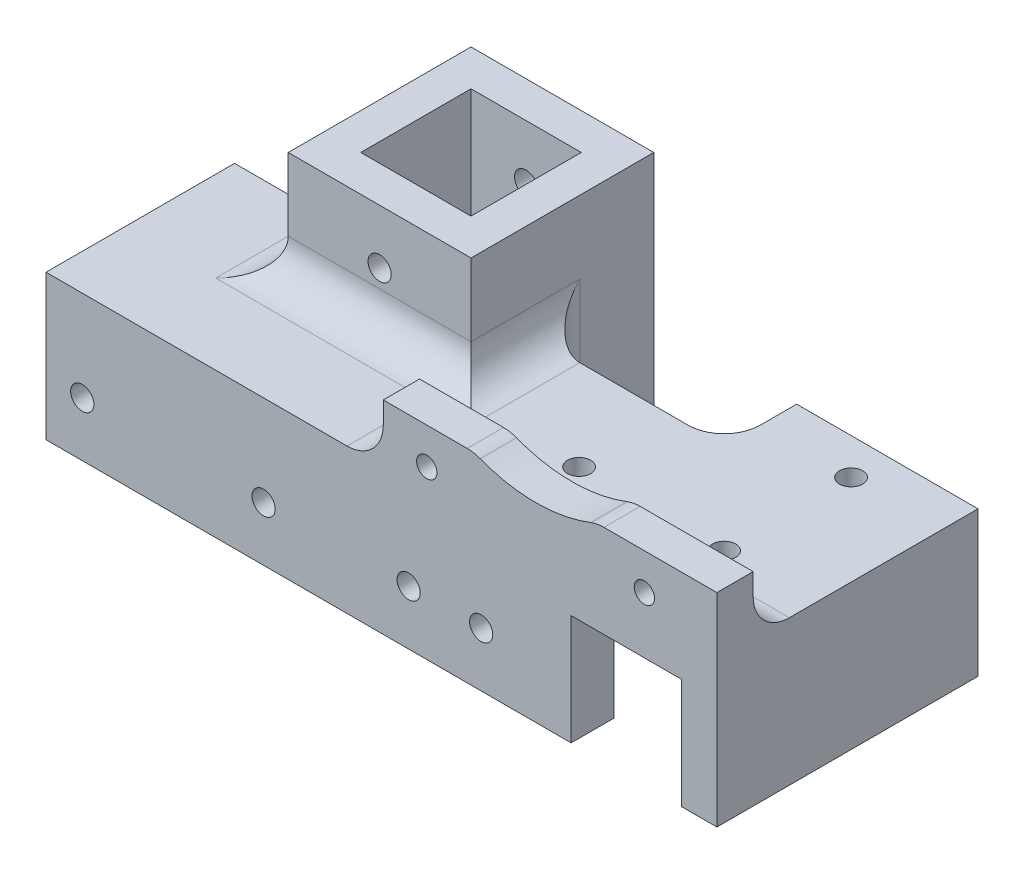
SolidWorks part; units mm, degrees
material "PLA"
ref_plane "前视基准面" through (0, 0, 0) normal (0, 0, 1) x (1, 0, 0)
ref_plane "上视基准面" through (0, 0, 0) normal (0, 1, 0) x (1, 0, 0)
ref_plane "右视基准面" through (0, 0, 0) normal (1, 0, 0) x (0, 0, -1)
sketch "草图1" plane through (0, 0, 0) normal (0, 1, 0) x (1, 0, 0)
  line L3 (-30, 12.5) -> (-12.6, 12.5)
  line L4 (-7.6, 22.7) -> (7.6, 22.7)
  line L5 (-7.6, 22.7) -> (-7.6, 7.5)
  line L6 (-7.6, 7.5) -> (7.6, 7.5)
  line L7 (7.6, 22.7) -> (7.6, 7.5)
  line L8 (-7.6, 22.7) -> (7.6, 7.5) construction
  line L9 (-7.6, 7.5) -> (7.6, 22.7) construction
  line L12 (50, -13.5) -> (50, 22.5) construction
  line L14 (-12.6, 27.7) -> (-12.6, 12.5)
  line L15 (-12.6, 27.7) -> (12.6, 27.7)
  line L16 (12.6, 27.7) -> (12.6, 12.5)
  line L17 (12.6, 27.7) -> (12.6, 7.5) construction
  line L18 (12.6, 12.5) -> (37.5, 12.5)
  line L20 (-12.6, 27.7) -> (-12.6, 7.5) construction
  line L29 (-30, 12.5) -> (-30, -13.5)
  line L32 (57.5, -13.5) -> (57.5, 22.5) construction
  line L33 (42.5, -13.5) -> (42.5, 22.5) construction
  line L34 (37.5, 12.5) -> (37.5, 22.5)
  line L35 (37.5, 22.5) -> (62.5, 22.5)
  line L36 (62.5, 22.5) -> (62.5, -13.5)
  line L37 (50, -13.5) -> (50, 22.5) construction
  line L38 (57.5, -13.5) -> (57.5, 22.5) construction
  line L39 (42.5, -13.5) -> (42.5, 22.5) construction
  line L40 (-30, -13.5) -> (62.5, -13.5)
  line L41 (-30, -7.5) -> (42.5, -7.5) construction
  line L42 (-30, 0) -> (50, 0) construction
  line L43 (-30, 7.5) -> (42.5, 7.5) construction
  point P9 (0, 15.1)
  dimension "D3" = 15.2
  dimension "D4" = 50
  dimension "D8" = 7.5
  dimension "D6" = 7.5
  dimension "D13" = 30
  dimension "D2" = 6
  dimension "D5" = 5
  dimension "D9" = 5
  dimension "D10" = 15
  dimension "D7" = 5
  dimension "D14" = 7.5
  dimension "D15" = 7.5
extrude "凸台-拉伸1" add sketch "草图1" along normal blind 20
sketch "草图2" plane through (0, 20, 0) normal (0, 1, 0) x (1, 0, 0)
  line L0 (7.6, 7.5) -> (7.6, 22.7) construction
  line L1 (7.6, 7.5) -> (7.6, 22.7)
  line L2 (-7.6, 7.5) -> (7.6, 7.5) construction
  line L3 (-7.6, 22.7) -> (-7.6, 7.5) construction
  line L4 (7.6, 22.7) -> (-7.6, 22.7) construction
  line L5 (-7.6, 7.5) -> (7.6, 7.5)
  line L6 (-7.6, 22.7) -> (-7.6, 7.5)
  line L7 (7.6, 22.7) -> (-7.6, 22.7)
  line L8 (-12.6, 27.7) -> (-12.6, 2.5)
  line L9 (-12.6, 2.5) -> (12.6, 2.5)
  line L10 (12.6, 2.5) -> (12.6, 27.7)
  line L11 (12.6, 27.7) -> (-12.6, 27.7)
  dimension "D1" = 5
extrude "凸台-拉伸2" add sketch "草图2" along normal blind 15
sketch "草图3" plane through (-30, 0, 0) normal (1, 0, 0) x (0, 0, -1)
  line L0 (-7.6, 0) -> (7.6, 0)
  line L1 (-7.6, 15.2) -> (7.6, 15.2)
  line L2 (-7.6, 15.2) -> (-7.6, 0)
  line L3 (-13.5, 0) -> (22.5, 0) construction
  line L4 (7.6, 15.2) -> (7.6, 0)
  point P4 (0, 15.2)
  dimension "D1" = 15.2
extrude "切除-拉伸1" cut sketch "草图3" along normal blind 80
sketch "草图4" plane through (0, 0, 13.5) normal (0, 0, 1) x (1, 0, 0)
  line L0 (-30, 7.5) -> (30, 7.5) construction
  line L2 (-30, 0) -> (62.5, 0) construction
  line L3 (0, 0) -> (0, 7.5) construction
  line L4 (0, 7.5) -> (0, 27.5) construction
  line L5 (-12.6, 35) -> (12.6, 35) construction
  line L6 (-30, 20) -> (-30, 0) construction
  circle A0 centre (0, 7.5) radius 1.6
  circle A1 centre (20, 7.5) radius 1.6
  circle A2 centre (-25, 7.5) radius 1.6
  circle A3 centre (0, 27.5) radius 1.6
  circle A4 centre (30, 7.5) radius 1.6
  dimension "D1" = 3.2
  dimension "D2" = 25
  dimension "D3" = 3.2
  dimension "D6" = 20
  dimension "D7" = 10
  dimension "D4" = 7.5
  dimension "D5" = 7.5
extrude "切除-拉伸2" cut sketch "草图4" against normal through all
fillet "圆角1" radius 5 6 edges at (12.6, 10, -12.5) (-12.6, 10, -12.5) (-12.6, 20, -7.5) (0, 20, -2.5) (12.6, 20, -7.5) (37.5, 10, -12.5)
sketch "草图5" plane through (0, 0, 13.5) normal (0, 0, 1) x (1, 0, 0)
  line L1 (42.4, 0) -> (57.6, 0)
  line L2 (42.4, 0) -> (42.4, 15.2)
  line L3 (42.4, 15.2) -> (57.6, 15.2)
  line L4 (57.6, 0) -> (57.6, 15.2)
  line L5 (-30, 0) -> (62.5, 0) construction
  point P6 (50, 0)
  dimension "D1" = 50
  dimension "D2" = 15.2
extrude "切除-拉伸3" cut sketch "草图5" against normal through all
sketch "草图7" plane through (0, 20, 0) normal (0, 1, 0) x (1, 0, 0)
  line L0 (0, 0) -> (50, 0) construction
  line L1 (50, 0) -> (50, 22.5) construction
  line L3 (62.5, 22.5) -> (37.5, 22.5) construction
  circle A0 centre (50, 0) radius 1.6
  circle A1 centre (30, 0) radius 1.6
  circle A2 centre (50, 17.5) radius 1.6
  dimension "D2" = 30
  dimension "D3" = 3.2
  dimension "D4" = 5
  dimension "D1" = 50
extrude "切除-拉伸5" cut sketch "草图7" against normal up to next
sketch "草图8" plane through (0, 20, 0) normal (0, 1, 0) x (1, 0, 0)
  line L1 (62.5, -13.5) -> (16.5, -13.5)
  line L2 (62.5, -13.5) -> (62.5, -8.5)
  line L3 (62.5, -8.5) -> (16.5, -8.5)
  line L4 (16.5, -13.5) -> (16.5, -8.5)
  dimension "D1" = 5
  dimension "D2" = 46
extrude "凸台-拉伸3" add sketch "草图8" along normal blind 8
fillet "圆角2" radius 5 1 edges at (39.5, 20, 8.5)
sketch "草图9" plane through (0, 0, 13.5) normal (0, 0, 1) x (1, 0, 0)
  line L0 (-30, 0) -> (42.4, 0) construction
  line L1 (62.5, 28) -> (62.5, 0) construction
  line L2 (37.5, 47.5) -> (37.5, 0) construction
  line L3 (22.5, 23) -> (52.5, 23) construction
  line L4 (16.5, 28) -> (62.5, 28) construction
  circle A0 centre (37.5, 47.5) radius 21.25
  circle A1 centre (22.5, 23) radius 1.4
  circle A2 centre (52.5, 23) radius 1.4
  point P10 (37.5, 23)
  dimension "D2" = 42.5
  dimension "D3" = 25
  dimension "D4" = 2.8
  dimension "D1" = 47.5
  dimension "D5" = 5
  dimension "D6" = 30
extrude "切除-拉伸6" cut sketch "草图9" against normal up to next
fillet "圆角3" radius 5 3 edges at (16.5, 20, 8.5) (45.9447, 28, 11) (29.0553, 28, 11)
